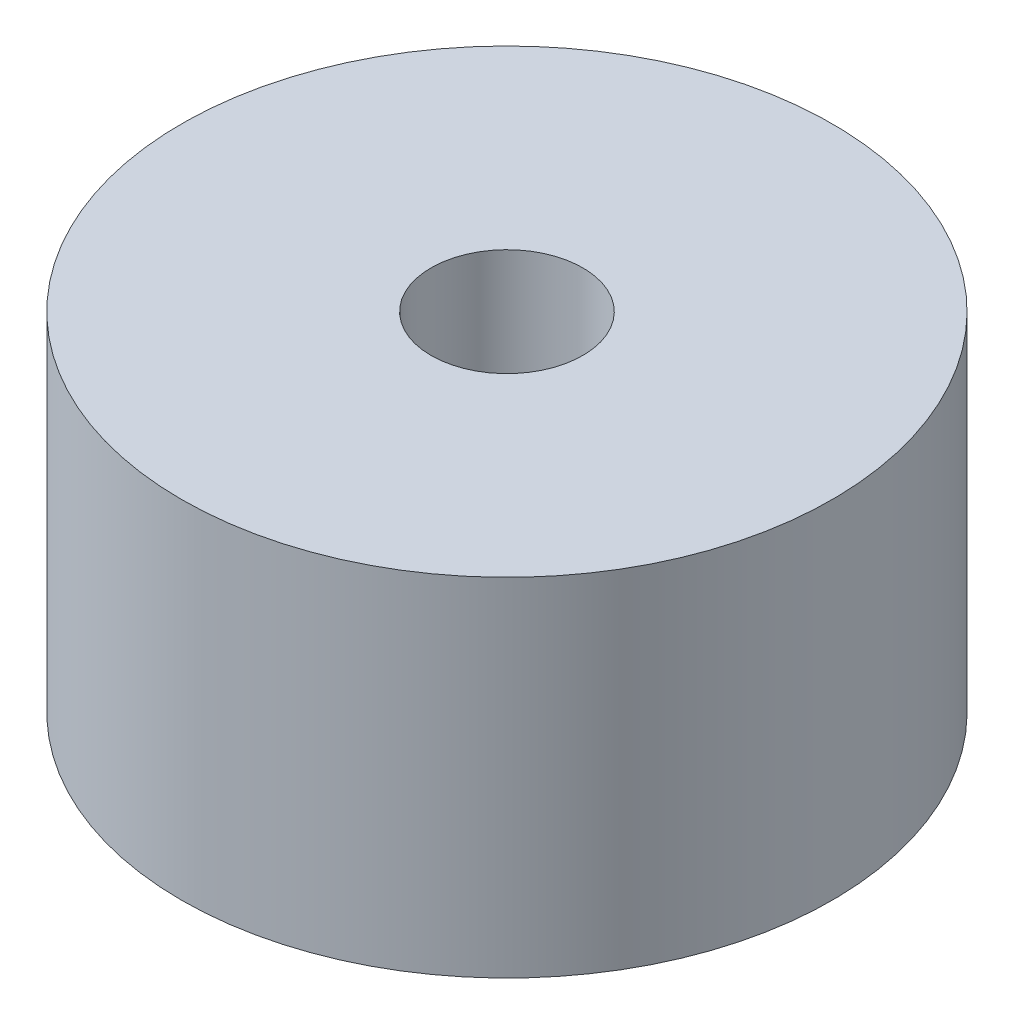
SolidWorks part; units mm, degrees
ref_plane "Front Plane" through (0, 0, 0) normal (0, 0, 1) x (1, 0, 0)
ref_plane "Top Plane" through (0, 0, 0) normal (0, 1, 0) x (1, 0, 0)
ref_plane "Right Plane" through (0, 0, 0) normal (1, 0, 0) x (0, 0, -1)
sketch "Sketch1" plane through (0, 0, 0) normal (0, 1, 0) x (1, 0, 0)
  circle A0 centre (0, 0) radius 1.75
  circle A2 centre (0, 0) radius 7.5
  dimension "D1" = 3.5
  dimension "D2" = 15
extrude "Boss-Extrude1" add sketch "Sketch1" along normal blind 8
